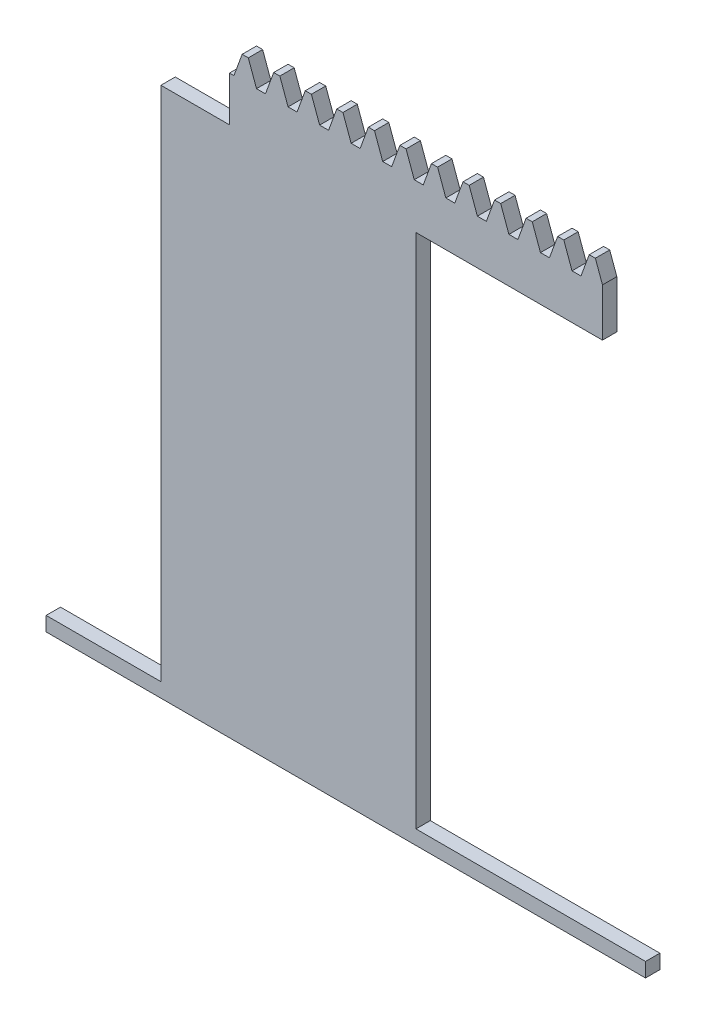
SolidWorks part; units mm, degrees
extrude "Blank" add sketch "BlankSke" against normal blind 1
sketch "BlankSke" plane through (0, 0, 0) normal (0, 0, 1) x (1, 0, 0)
  line L1 (0, 0) -> (26, 0)
  line L2 (0, 0) -> (0, 4.7)
  line L3 (0, 4.7) -> (26, 4.7)
  line L4 (26, 0) -> (26, 4.7)
  dimension "Length" = 26
  dimension "Blank_height" = 4.7
ref_plane "Plane1" through (0, 0, 0) normal (0, 0, 1) x (1, 0, 0)
ref_plane "Plane2" through (0, 0, 0) normal (0, 1, 0) x (1, 0, 0)
ref_plane "Plane3" through (0, 0, 0) normal (1, 0, 0) x (0, 0, -1)
other "Configuration Table"
sketch "HoldingSke" plane through (0, 0, 0) normal (0, 1, 0) x (1, 0, 0)
  line L0 (0, 0) -> (0.1988, 1.4147)
  line L1 (-15, 0) -> (100, 0) construction
  line L2 (0, 0) -> (-2.1039, 2.3779)
  line L3 (0, 0) -> (-11.863, 4.5341)
  line L4 (0, 0) -> (8.4147, 1.9427)
  line L5 (0, 0) -> (-23.7986, -8.8762)
  line L6 (0, 0) -> (-10.5278, -7.1032)
  line L9 (-71.009, 38.7566) -> (-47.5167, 47.3071)
  line L10 (-76.2, 3.0779) -> (-72.2, 3.0779)
  line L11 (0, 0) -> (-1, 0)
  line L12 (-76.2, 101.6) -> (-76.173, 101.6)
  line L13 (24.9733, 27.94) -> (52.9518, 28.4284)
  line L14 (24.9733, 27.94) -> (24.9743, 27.94)
  line L15 (24.9733, 27.94) -> (100.4006, 29.5858)
  circle A0 centre (0, 0) radius 19.05
  circle A1 centre (0, 0) radius 2
  circle A2 centre (0, 0) radius 12.7
  dimension "MPH" = 4
  dimension "Diameter" = 38.1
  dimension "Num_teeth" = 13
  dimension "Pitch" = 1.4286
  dimension "Show_teeth" = 998
  dimension "Thickness" = 12.7
  dimension "Ap" = 20
  dimension "Pitch_height" = 4
  dimension "Width" = 1
  dimension "Backlash" = 0.027
  dimension "Addendum_fac" = 1
  dimension "Dedendum_fac" = 1.25
  dimension "Clearance_fac" = 0.25
  dimension "Dedendum_add" = 0.001
  dimension "Length" = 25
  dimension "Module" = 0.7
sketch "TooCutSkeIll" plane through (0, 0, 0) normal (0, 0, 1) x (1, 0, 0)
  line L0 (-0.8789, 4.6816) -> (-0.3545, 3.2408)
  line L1 (-0.1891, 3.125) -> (0.1891, 3.125)
  line L2 (0.3545, 3.2408) -> (0.8789, 4.6816)
  line L3 (26, 4.7) -> (0, 4.7) construction
  line L4 (0, 0) -> (0, 64.897) construction
  line L5 (-13.208, 4) -> (12.954, 4) construction
  line L6 (0, 0) -> (26, 0) construction
  line L7 (0.6308, 4) -> (0.6308, 48.7463) construction
  line L8 (-0.6308, 4) -> (-0.6308, 48.7463) construction
  line L9 (0.9052, 4.7) -> (0.9052, 4.7254)
  line L10 (-0.9052, 4.7) -> (-0.9052, 4.7254)
  line L11 (-0.9052, 4.7254) -> (0.9052, 4.7254)
  arc A0 (0.1891, 3.125) -> (0.3545, 3.2408) centre (0.1891, 3.301) ccw
  arc A1 (-0.3545, 3.2408) -> (-0.1891, 3.125) centre (-0.1891, 3.301) ccw
  arc A2 (0.9052, 4.7) -> (0.8789, 4.6816) centre (0.9052, 4.672) ccw
  arc A3 (-0.8789, 4.6816) -> (-0.9052, 4.7) centre (-0.9052, 4.672) ccw
  dimension "Pitch_height" = 4
  dimension "Addendum_plus" = 0.7254
  dimension "Pressure_angle" = 20
  dimension "Gap_width" = 1.2616
  dimension "Dedendum" = 0.875
extrude "ToothCutIll" [suppressed] cut sketch "TooCutSkeIll" against normal through all
sketch "TooCutSkeSim" plane through (0, 0, 0) normal (0, 0, 1) x (1, 0, 0)
  line L0 (0.3123, 3.125) -> (-0.3123, 3.125)
  line L1 (0.8948, 4.7254) -> (0.3123, 3.125)
  line L2 (0, 17.4625) -> (0, 53.467) construction
  line L3 (0.8948, 4.7254) -> (-0.8948, 4.7254)
  line L6 (-0.8948, 4.7254) -> (-0.3123, 3.125)
  line L9 (-0.6308, 4) -> (0.6308, 4) construction
  line L10 (0, 0) -> (26, 0) construction
  line L11 (0.6308, 4) -> (0.6308, 53.467) construction
  line L12 (-0.6308, 4) -> (-0.6308, 53.467) construction
  dimension "Pitch_height" = 4
  dimension "Addendum_plus" = 0.7254
  dimension "Pressure_angle" = 20
  dimension "Gap_width" = 1.2616
  dimension "Dedendum" = 0.875
extrude "ToothCutSim" cut sketch "TooCutSkeSim" against normal through all
pattern_linear "TeethCuts" count 12 spacing 2.1991 along (1, 0, 0) of "ToothCutIll", "ToothCutSim"
sketch "Sketch3" plane through (0, 0, 0) normal (0, -1, 0) x (1, 0, 0)
  line L0 (0, 0) -> (26, 0) construction
  line L1 (13, 0) -> (-4.7757, 0)
  line L2 (13, 0) -> (13, -1)
  line L3 (13, -1) -> (-4.7757, -1)
  line L4 (-4.7757, 0) -> (-4.7757, -1)
  line L5 (0, -1) -> (26, -1) construction
extrude "Boss-Extrude2" add sketch "Sketch3" along normal blind 37
sketch "Sketch4" plane through (13, 0, 0) normal (1, 0, 0) x (0, 0, -1)
  line L0 (1, -37) -> (1, 0) construction
  line L1 (0, -37) -> (1, -37)
  line L2 (0, -37) -> (0, -36)
  line L3 (0, -36) -> (1, -36)
  line L4 (1, -37) -> (1, -36)
  dimension "D1" = 1
extrude "Boss-Extrude3" add sketch "Sketch4" along normal blind 16 and the other way offset from surface (25.7757 mm away) 8 other way up to face at (-4.7757, -18.5, -0.5)
equation "' \"Module@HoldingSke\" = 6.35"
equation "' \"Num_teeth@HoldingSke\" = 12"
equation "' \"Ap@HoldingSke\" =  20"
equation "' \"Ap@HoldingSke\" = 20"
equation "' \"Width@HoldingSke\" = 0.25 * 25.4"
equation "' \"Show_teeth@HoldingSke\" = 500"
equation "' \"Backlash@HoldingSke\" = 0.009 * 25.4"
equation "' \"Addendum_fac@HoldingSke\" = 1.0"
equation "' \"Dedendum_fac@HoldingSke\" = 1.25"
equation "' \"Dedendum_add@HoldingSke\" = 0.00005 * 25.4"
equation "' \"Clearance_fac@HoldingSke\" = 0.25"
equation "' \"Pitch_height@HoldingSke\" = 1 * 25.4"
equation "' \"Length@HoldingSke\" = 4.71 * 25.4"
equation "\"Pitch@HoldingSke\" = 1 / \"Module@HoldingSke\""
equation "\"MPH@HoldingSke\" = \"Dedendum_fac@HoldingSke\" / \"Pitch@HoldingSke\" + 2 * \"Dedendum_add@HoldingSke\" + 0.002 * 25.4"
equation "\"MPH@HoldingSke\" = ((sgn( \"MPH@HoldingSke\" - \"Pitch_height@HoldingSke\")+1)*( \"MPH@HoldingSke\" - \"Pitch_height@HoldingSke\"))/2 + \"Pitch_height@HoldingSke\""
equation "\"Blank_height@BlankSke\" = \"Pitch_height@HoldingSke\" + \"Addendum_fac@HoldingSke\"  / \"Pitch@HoldingSke\" "
equation "\"Pressure_angle@TooCutSkeIll\" = \"Ap@HoldingSke\""
equation "\"Addendum_plus@TooCutSkeIll\" =  \"Addendum_fac@HoldingSke\"  / \"Pitch@HoldingSke\" + 0.001 *25.4"
equation "\"Dedendum@TooCutSkeIll\" = \"Dedendum_fac@HoldingSke\"  / \"Pitch@HoldingSke\""
equation "\"Pitch_height@TooCutSkeIll\" =  \"MPH@HoldingSke\""
equation "\"Gap_width@TooCutSkeIll\" = 3.14159265 / 2 / \"Pitch@HoldingSke\" + 6 * \"Backlash@HoldingSke\""
equation "\"Pressure_angle@TooCutSkeSim\" = \"Ap@HoldingSke\""
equation "\"Addendum_plus@TooCutSkeSim\" =  \"Addendum_fac@HoldingSke\"  / \"Pitch@HoldingSke\" + 0.001 * 25.4"
equation "\"Dedendum@TooCutSkeSim\" = \"Dedendum_fac@HoldingSke\"  / \"Pitch@HoldingSke\""
equation "\"Pitch_height@TooCutSkeSim\" =  \"MPH@HoldingSke\""
equation "\"Gap_width@TooCutSkeSim\" = 3.14159265 / 2 / \"Pitch@HoldingSke\" + 6 * \"Backlash@HoldingSke\""
equation "\"Root_fillet@TooCutSkeIll\" = \"Clearance_fac@HoldingSke\" / \"Pitch@HoldingSke\" + \"Dedendum_add@HoldingSke\""
equation "\"Break_rad@TooCutSkeIll\" = 0.02 / \"Pitch@HoldingSke\" * 2"
equation "\"Linear_pitch@TeethCuts\" = 3.14159265 / \"Pitch@HoldingSke\""
equation "\"Num_teeth@HoldingSke\" = int( ( \"Length@HoldingSke\" + 0 ) / (3.14159265 / \"Pitch@HoldingSke\")) + 0.9999  + 1"
equation " \"Num_teeth@TeethCuts\" = int( \"Show_teeth@HoldingSke\" ) + 1"
equation " \"Num_teeth@TeethCuts\" = ((sgn( \"Num_teeth@TeethCuts\" - \"Num_teeth@HoldingSke\" )-1)*( \"Num_teeth@TeethCuts\" - \"Num_teeth@HoldingSke\" ))/-2+ \"Num_teeth@HoldingSke\""
equation " \"Num_teeth@TeethCuts\" = ((sgn( \"Num_teeth@TeethCuts\" - 2.0)+1)*( \"Num_teeth@TeethCuts\" - 2.0))/2 +2.0"
